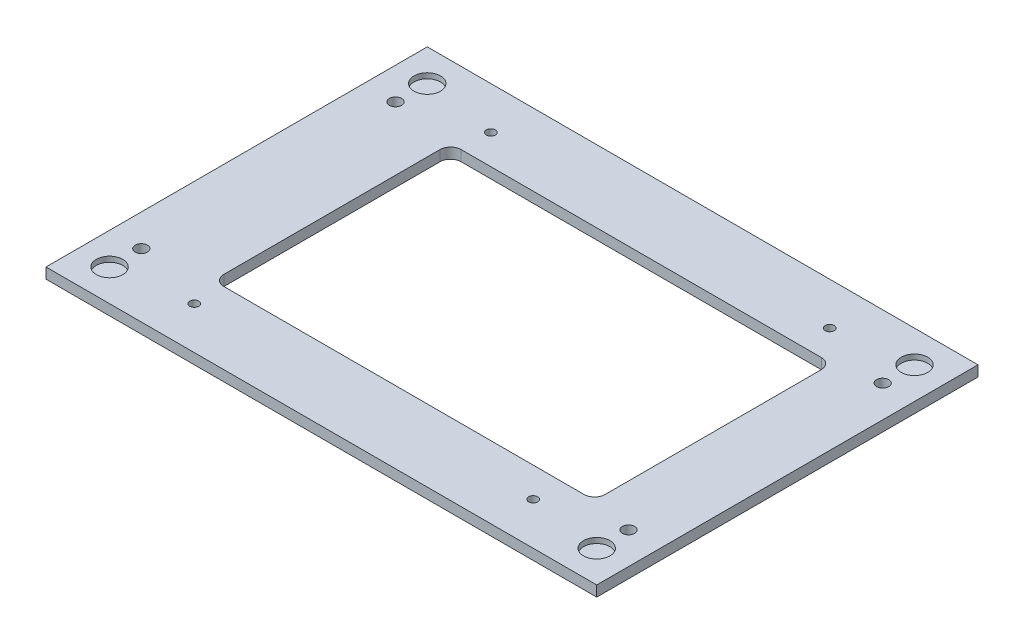
SolidWorks part; units mm, degrees
material "6061 Alloy"
ref_plane "Front Plane" through (0, 0, 0) normal (0, 0, 1) x (1, 0, 0)
ref_plane "Top Plane" through (0, 0, 0) normal (0, 1, 0) x (1, 0, 0)
ref_plane "Right Plane" through (0, 0, 0) normal (1, 0, 0) x (0, 0, -1)
sketch "Sketch1" plane through (0, 0, 0) normal (0, 1, 0) x (1, 0, 0)
  line L1 (-82.55, -57.15) -> (82.55, -57.15)
  line L2 (-82.55, -57.15) -> (-82.55, 57.15)
  line L3 (-82.55, 57.15) -> (82.55, 57.15)
  line L4 (82.55, -57.15) -> (82.55, 57.15)
  line L5 (-82.55, -57.15) -> (82.55, 57.15) construction
  line L6 (-82.55, 57.15) -> (82.55, -57.15) construction
  point P0 (0, 0)
  dimension "D1" = 165.1
  dimension "D2" = 114.3
extrude "Boss-Extrude1" add sketch "Sketch1" along normal blind 3.175
sketch "Sketch2" plane through (0, 3.175, 0) normal (0, 1, 0) x (1, 0, 0)
  line L0 (-49.5, -31.5) -> (-40.5, -31.4997) construction
  line L1 (-49.5, -31.5) -> (-49.5008, -22.5) construction
  line L2 (-82.55, 57.15) -> (-82.55, -57.15) construction
  line L3 (-82.55, -57.15) -> (82.55, -57.15) construction
  line L4 (-49.5, -31.5) -> (-49.5, 44.7) construction
  line L5 (-49.5, -31.5) -> (77.5, -31.5) construction
  line L6 (82.55, -57.15) -> (82.55, 57.15) construction
  line L9 (82.55, 57.15) -> (-82.55, 57.15) construction
  line L10 (0, 57.15) -> (0, -57.15) construction
  line L11 (-82.55, 0) -> (82.55, 0) construction
  circle A0 centre (-49.5, -31.5) radius 0.89
  circle A96 centre (-40.5, -31.4997) radius 0.89
  circle A97 centre (-31.5, -31.4993) radius 0.89
  circle A98 centre (-22.5, -31.499) radius 0.89
  circle A99 centre (-13.5, -31.4987) radius 0.89
  circle A100 centre (-4.5, -31.4983) radius 0.89
  circle A101 centre (4.5, -31.498) radius 0.89
  circle A102 centre (13.5, -31.4977) radius 0.89
  circle A103 centre (22.5, -31.4973) radius 0.89
  circle A104 centre (31.5, -31.497) radius 0.89
  circle A105 centre (40.5, -31.4967) radius 0.89
  circle A106 centre (49.5, -31.4963) radius 0.89
  circle A107 centre (58.5, -31.496) radius 0.89
  circle A108 centre (-49.5008, -22.5) radius 0.89
  circle A109 centre (-40.5008, -22.4997) radius 0.89
  circle A110 centre (-31.5008, -22.4993) radius 0.89
  circle A111 centre (-22.5008, -22.499) radius 0.89
  circle A112 centre (-13.5008, -22.4987) radius 0.89
  circle A113 centre (-4.5008, -22.4983) radius 0.89
  circle A114 centre (4.4992, -22.498) radius 0.89
  circle A115 centre (13.4992, -22.4977) radius 0.89
  circle A116 centre (22.4992, -22.4973) radius 0.89
  circle A117 centre (31.4992, -22.497) radius 0.89
  circle A118 centre (40.4992, -22.4967) radius 0.89
  circle A119 centre (49.4992, -22.4963) radius 0.89
  circle A120 centre (58.4992, -22.496) radius 0.89
  circle A121 centre (-49.5015, -13.5) radius 0.89
  circle A122 centre (-40.5015, -13.4997) radius 0.89
  circle A123 centre (-31.5015, -13.4993) radius 0.89
  circle A124 centre (-22.5015, -13.499) radius 0.89
  circle A125 centre (-13.5015, -13.4987) radius 0.89
  circle A126 centre (-4.5015, -13.4983) radius 0.89
  circle A127 centre (4.4985, -13.498) radius 0.89
  circle A128 centre (13.4985, -13.4977) radius 0.89
  circle A129 centre (22.4985, -13.4973) radius 0.89
  circle A130 centre (31.4985, -13.497) radius 0.89
  circle A131 centre (40.4985, -13.4967) radius 0.89
  circle A132 centre (49.4985, -13.4963) radius 0.89
  circle A133 centre (58.4985, -13.496) radius 0.89
  circle A134 centre (-49.5023, -4.5) radius 0.89
  circle A135 centre (-40.5023, -4.4997) radius 0.89
  circle A136 centre (-31.5023, -4.4993) radius 0.89
  circle A137 centre (-22.5023, -4.499) radius 0.89
  circle A138 centre (-13.5023, -4.4987) radius 0.89
  circle A139 centre (-4.5023, -4.4983) radius 0.89
  circle A140 centre (4.4977, -4.498) radius 0.89
  circle A141 centre (13.4977, -4.4977) radius 0.89
  circle A142 centre (22.4977, -4.4973) radius 0.89
  circle A143 centre (31.4977, -4.497) radius 0.89
  circle A144 centre (40.4977, -4.4967) radius 0.89
  circle A145 centre (49.4977, -4.4963) radius 0.89
  circle A146 centre (58.4977, -4.496) radius 0.89
  circle A147 centre (-49.5031, 4.5) radius 0.89
  circle A148 centre (-40.5031, 4.5003) radius 0.89
  circle A149 centre (-31.5031, 4.5007) radius 0.89
  circle A150 centre (-22.5031, 4.501) radius 0.89
  circle A151 centre (-13.5031, 4.5013) radius 0.89
  circle A152 centre (-4.5031, 4.5017) radius 0.89
  circle A153 centre (4.4969, 4.502) radius 0.89
  circle A154 centre (13.4969, 4.5023) radius 0.89
  circle A155 centre (22.4969, 4.5027) radius 0.89
  circle A156 centre (31.4969, 4.503) radius 0.89
  circle A157 centre (40.4969, 4.5033) radius 0.89
  circle A158 centre (49.4969, 4.5037) radius 0.89
  circle A159 centre (58.4969, 4.504) radius 0.89
  circle A160 centre (-49.5038, 13.5) radius 0.89
  circle A161 centre (-40.5038, 13.5003) radius 0.89
  circle A162 centre (-31.5038, 13.5007) radius 0.89
  circle A163 centre (-22.5038, 13.501) radius 0.89
  circle A164 centre (-13.5038, 13.5013) radius 0.89
  circle A165 centre (-4.5038, 13.5017) radius 0.89
  circle A166 centre (4.4962, 13.502) radius 0.89
  circle A167 centre (13.4962, 13.5023) radius 0.89
  circle A168 centre (22.4962, 13.5027) radius 0.89
  circle A169 centre (31.4962, 13.503) radius 0.89
  circle A170 centre (40.4962, 13.5033) radius 0.89
  circle A171 centre (49.4962, 13.5037) radius 0.89
  circle A172 centre (58.4962, 13.504) radius 0.89
  circle A173 centre (-49.5046, 22.5) radius 0.89
  circle A174 centre (-40.5046, 22.5003) radius 0.89
  circle A175 centre (-31.5046, 22.5007) radius 0.89
  circle A176 centre (-22.5046, 22.501) radius 0.89
  circle A177 centre (-13.5046, 22.5013) radius 0.89
  circle A178 centre (-4.5046, 22.5017) radius 0.89
  circle A179 centre (4.4954, 22.502) radius 0.89
  circle A180 centre (13.4954, 22.5023) radius 0.89
  circle A181 centre (22.4954, 22.5027) radius 0.89
  circle A182 centre (31.4954, 22.503) radius 0.89
  circle A183 centre (40.4954, 22.5033) radius 0.89
  circle A184 centre (49.4954, 22.5037) radius 0.89
  circle A185 centre (58.4954, 22.504) radius 0.89
  circle A186 centre (-49.5054, 31.5) radius 0.89
  circle A187 centre (-40.5054, 31.5003) radius 0.89
  circle A188 centre (-31.5054, 31.5007) radius 0.89
  circle A189 centre (-22.5054, 31.501) radius 0.89
  circle A190 centre (-13.5054, 31.5013) radius 0.89
  circle A191 centre (-4.5054, 31.5017) radius 0.89
  circle A192 centre (4.4946, 31.502) radius 0.89
  circle A193 centre (13.4946, 31.5023) radius 0.89
  circle A194 centre (22.4946, 31.5027) radius 0.89
  circle A195 centre (31.4946, 31.503) radius 0.89
  circle A196 centre (40.4946, 31.5033) radius 0.89
  circle A197 centre (49.4946, 31.5037) radius 0.89
  circle A198 centre (58.4946, 31.504) radius 0.89
  dimension "D1" = 13
  dimension "D7" = 1.78
  dimension "D3" = 9
  dimension "D4" = 9
  dimension "D5" = 49.5
  dimension "D6" = 31.5
  dimension "D9" = 33.0454
  dimension "D11" = 25.654
  dimension "D13" = 127
  dimension "D14" = 76.2
  dimension "D2" = 8
sketch "Sketch3" plane through (0, 3.175, 0) normal (0, 1, 0) x (1, 0, 0)
  line L0 (82.55, 57.15) -> (-82.55, 57.15) construction
  line L1 (-82.55, 57.15) -> (-82.55, -57.15) construction
  line L2 (-82.55, -57.15) -> (82.55, -57.15) construction
  line L3 (82.55, -57.15) -> (82.55, 57.15) construction
  circle A0 centre (-73.025, 47.625) radius 3.9687
  circle A1 centre (-73.025, -47.625) radius 3.9687
  circle A2 centre (73.025, 47.625) radius 3.9687
  circle A3 centre (73.025, -47.625) radius 3.9687
  dimension "D1" = 7.9375
  dimension "D2" = 7.9375
  dimension "D3" = 7.9375
  dimension "D4" = 7.9375
  dimension "D5" = 9.525
  dimension "D6" = 9.525
  dimension "D7" = 9.525
  dimension "D8" = 9.525
  dimension "D9" = 9.525
  dimension "D10" = 9.525
  dimension "D11" = 9.525
  dimension "D12" = 9.525
extrude "Cut-Extrude2" cut sketch "Sketch3" against normal blind 1.5875
hole_wizard "#6-32 Tapped Hole1" positions "Sketch10" profile "Sketch9" tap size "#6-32" standard "Ansi Inch" end condition through all
sketch "Sketch10" plane through (0, 3.175, 0) normal (0, 1, 0) x (-1, 0, 0)
  line L0 (-82.55, -57.15) -> (82.55, -57.15) construction
  line L1 (82.55, -57.15) -> (82.55, 57.15) construction
  line L2 (-82.55, 57.15) -> (-82.55, -57.15) construction
  line L3 (82.55, 57.15) -> (-82.55, 57.15) construction
  point P0 (50.8, -44.45)
  point P1 (-50.8, -44.45)
  point P3 (-50.8, 44.45)
  point P5 (50.8, 44.45)
  dimension "D1" = 12.7
  dimension "D2" = 31.75
  dimension "D3" = 12.7
  dimension "D4" = 31.75
  dimension "D5" = 12.7
  dimension "D6" = 31.75
  dimension "D7" = 12.7
  dimension "D8" = 31.75
sketch "Sketch9" plane through (-50.8, 3.175, -44.45) normal (1, 0, 0) x (0, 0, 1)
  line L0 (0, 0) -> (0, 3.175)
  line L1 (0, 3.175) -> (1.3525, 3.175)
  line L2 (1.3525, 3.175) -> (1.3525, 0)
  line L5 (1.3525, 0) -> (0, 0)
  line L11 (0, -6.35) -> (0, 107.95) construction
  dimension "Thru Tap Drill Dia." = 2.7051
  dimension "Thru Tap Drill Depth" = 3.175
cosmetic thread "Hole Thread3" parameters "D2"=3.5052
cosmetic thread "Hole Thread4" parameters "D2"=3.5052
cosmetic thread "Hole Thread5" parameters "D2"=3.5052
cosmetic thread "Hole Thread6" parameters "D2"=3.5052
sketch "Sketch11" plane through (0, 3.175, 0) normal (0, 1, 0) x (1, 0, 0)
  line L1 (-53.975, -35.56) -> (53.975, -35.56)
  line L2 (-53.975, -35.56) -> (-53.975, 35.56)
  line L3 (-53.975, 35.56) -> (53.975, 35.56)
  line L4 (53.975, -35.56) -> (53.975, 35.56)
  line L5 (-53.975, -35.56) -> (53.975, 35.56) construction
  line L6 (-53.975, 35.56) -> (53.975, -35.56) construction
  line L7 (53.975, 35.56) -> (60.325, 35.56)
  line L8 (53.975, 35.56) -> (53.975, -35.56)
  line L9 (53.975, -35.56) -> (60.325, -35.56)
  line L10 (60.325, 35.56) -> (60.325, -35.56)
  point P0 (0, 0)
  dimension "D1" = 107.95
  dimension "D2" = 71.12
  dimension "D3" = 6.35
extrude "Cut-Extrude3" cut sketch "Sketch11" against normal through all contours L1 L4 L3 L2 | L10 L7 L4 L9
fillet "Fillet1" radius 3.175 4 edges at (60.325, 1.5875, 35.56) (60.325, 1.5875, -35.56) (-53.975, 1.5875, 35.56) (-53.975, 1.5875, -35.56)
hole_wizard "#27 (0.144) Diameter Hole1" positions "Sketch13" profile "Sketch12" hole size "#27" standard "Ansi Inch"
sketch "Sketch13" plane through (0, 3.175, 0) normal (0, 1, 0) x (-1, 0, 0)
  line L0 (82.55, -57.15) -> (82.55, 57.15) construction
  line L1 (-82.55, -57.15) -> (82.55, -57.15) construction
  line L2 (82.55, 57.15) -> (-82.55, 57.15) construction
  line L3 (-82.55, 57.15) -> (-82.55, -57.15) construction
  point P0 (73.025, -38.1)
  point P1 (73.025, 38.1)
  point P3 (-73.025, -38.1)
  point P5 (-73.025, 38.1)
  dimension "D1" = 9.525
  dimension "D2" = 19.05
  dimension "D3" = 19.05
  dimension "D4" = 9.525
  dimension "D5" = 19.05
  dimension "D6" = 9.525
  dimension "D7" = 9.525
  dimension "D8" = 19.05
sketch "Sketch12" plane through (-73.025, 3.175, -38.1) normal (1, 0, 0) x (0, 0, 1)
  line L0 (0, 0) -> (0, 4.4009)
  line L1 (0, 4.4009) -> (1.8288, 3.302)
  line L2 (1.8288, 3.302) -> (1.8288, 0)
  line L5 (1.8288, 0) -> (0, 0)
  line L10 (0, 4.4009) -> (-1.8288, 3.302) construction
  line L11 (0, -6.35) -> (0, 107.95) construction
  dimension "Hole Dia." = 3.6576
  dimension "Hole Depth" = 3.302
  dimension "Drill Angle" = 118
sketch "Sketch14" plane through (0, 3.175, 0) normal (0, 1, 0) x (-1, 0, 0)
  line L0 (-82.55, -57.15) -> (82.55, -57.15) construction
  line L1 (63.5, -57.15) -> (-63.5, -57.15)
  line L2 (63.5, -57.15) -> (63.5, 57.15)
  line L3 (63.5, 57.15) -> (-63.5, 57.15)
  line L4 (-63.5, -57.15) -> (-63.5, 57.15)
  line L5 (82.55, 57.15) -> (-82.55, 57.15) construction
  line L6 (82.55, -57.15) -> (82.55, 57.15) construction
  line L7 (-82.55, 57.15) -> (-82.55, -57.15) construction
  circle A0 centre (50.8, -44.45) radius 1.3526 construction
  circle A1 centre (-50.8, -44.45) radius 1.3526 construction
  dimension "D4" = 12.7
  dimension "D5" = 12.7
  dimension "D6" = 12.7
  dimension "D1" = 127
  dimension "D2" = 19.05
  dimension "D3" = 114.3
  dimension "D7" = 12.7
  dimension "D8" = 19.05
equation "\"D6@Sketch3\" = \"D5@Sketch3\""
equation "\"D11@Sketch3\"=\"D5@Sketch3\""
equation "\"D12@Sketch3\"=\"D5@Sketch3\""
equation "\"D7@Sketch3\"=\"D5@Sketch3\""
equation "\"D8@Sketch3\"=\"D5@Sketch3\""
equation "\"D10@Sketch3\"=\"D5@Sketch3\""
equation "\"D9@Sketch3\" = \"D5@Sketch3\""
equation "\"D3@Sketch3\"=\"D1@Sketch3\""
equation "\"D2@Sketch3\" = \"D1@Sketch3\""
equation "\"D4@Sketch3\" = \"D1@Sketch3\""
equation "\"D3@Sketch13\" = \"D2@Sketch13\""
equation "\"D4@Sketch13\" = \"D1@Sketch13\""
equation "\"D5@Sketch13\" = \"D2@Sketch13\""
equation "\"D6@Sketch13\"=\"D1@Sketch13\""
equation "\"D7@Sketch13\"=\"D1@Sketch13\""
equation "\"D8@Sketch13\"=\"D2@Sketch13\""
